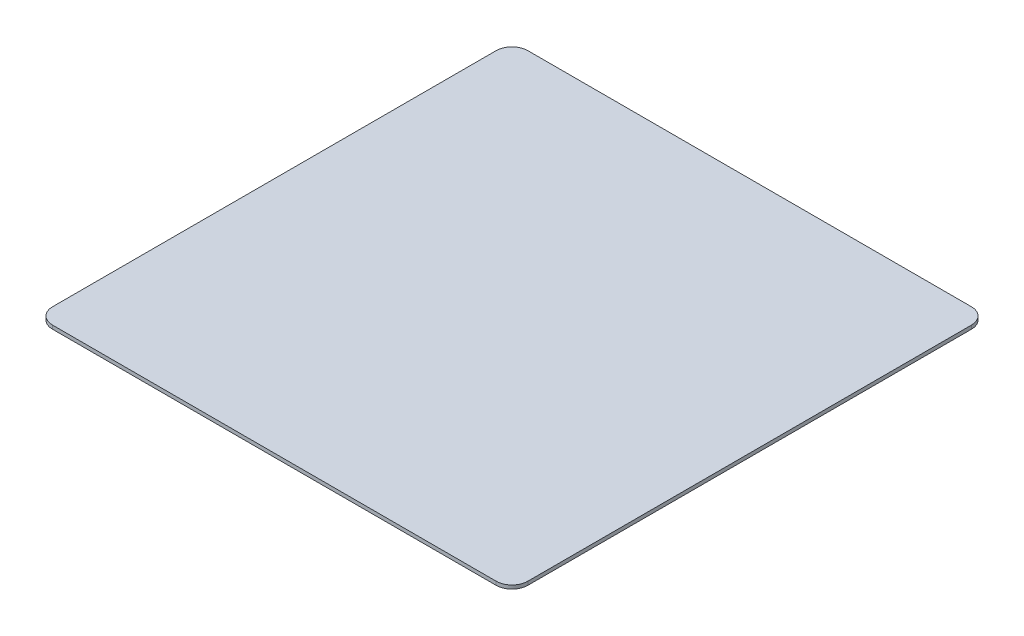
SolidWorks part; units mm, degrees
material "5052-O"
ref_plane "Front Plane" through (0, 0, 0) normal (0, 0, 1) x (1, 0, 0)
ref_plane "Top Plane" through (0, 0, 0) normal (0, 1, 0) x (1, 0, 0)
ref_plane "Right Plane" through (0, 0, 0) normal (1, 0, 0) x (0, 0, -1)
sketch "Sketch1" plane through (0, 0, 0) normal (0, 1, 0) x (1, 0, 0)
  line L1 (150, -150) -> (-150, -150)
  line L2 (150, -150) -> (150, 150)
  line L3 (150, 150) -> (-150, 150)
  line L4 (-150, -150) -> (-150, 150)
  line L5 (150, -150) -> (-150, 150) construction
  line L6 (150, 150) -> (-150, -150) construction
  point P0 (0, 0)
  dimension "D1" = 300
extrude "Boss-Extrude1" add sketch "Sketch1" along normal blind 2.286
fillet "Fillet1" radius 10 4 edges at (150, 1.143, -150) (150, 1.143, 150) (-150, 1.143, -150) (-150, 1.143, 150)
